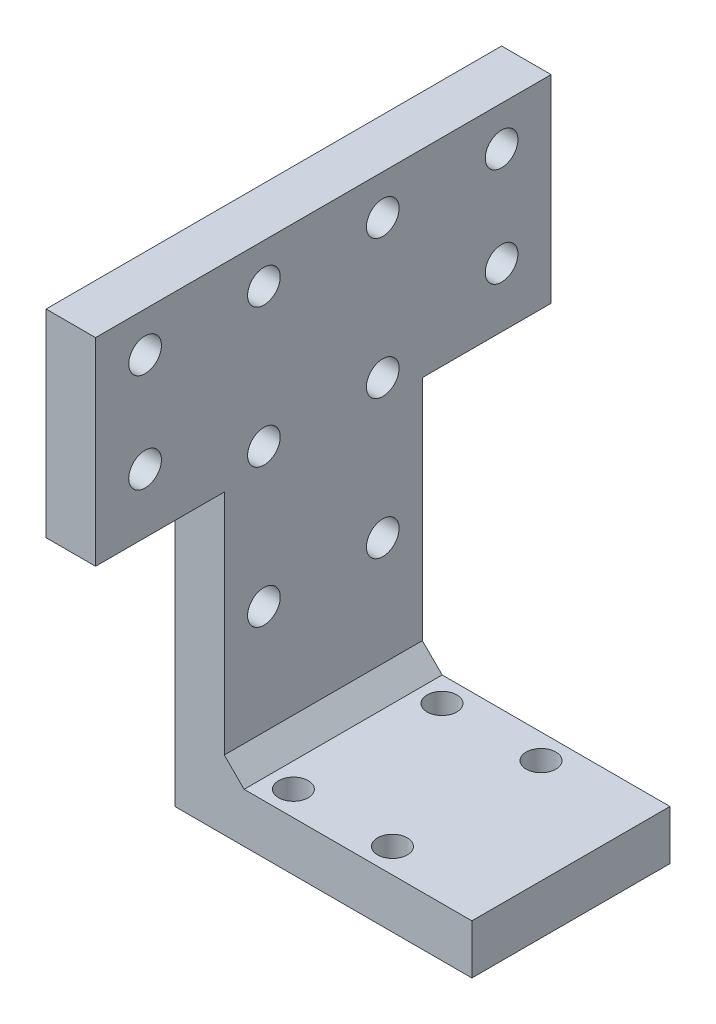
SolidWorks part; units mm, degrees
ref_plane "前视基准面" through (0, 0, 0) normal (0, 0, 1) x (1, 0, 0)
ref_plane "上视基准面" through (0, 0, 0) normal (0, 1, 0) x (1, 0, 0)
ref_plane "右视基准面" through (0, 0, 0) normal (1, 0, 0) x (0, 0, -1)
other "Configuration Table"
sketch "草图1" plane through (0, 0, 0) normal (0, 0, 1) x (1, 0, 0)
  line L0 (0, 50) -> (0, 0)
  line L1 (0, 0) -> (30, 0)
  line L2 (30, 0) -> (30, 5)
  line L3 (30, 5) -> (7, 5)
  line L4 (5, 7) -> (5, 50)
  line L5 (5, 50) -> (0, 50)
  line L6 (5, 7) -> (7, 5)
  dimension "D1" = 30
  dimension "D2" = 50
  dimension "D3" = 5
  dimension "D4" = 5
  dimension "D5" = 45
  dimension "D6" = 2
extrude "凸台-拉伸1" add sketch "草图1" along normal blind 20
sketch "草图2" plane through (0, 5, 0) normal (0, 1, 0) x (1, 0, 0)
  circle A1 centre (9.48, -17.5) radius 1.5
  circle A2 centre (9.48, -17.5) radius 1.5
  circle A3 centre (19.48, -17.5) radius 1.5
  circle A4 centre (19.48, -17.5) radius 1.5
  circle A5 centre (19.48, -2.5) radius 1.5
  circle A6 centre (19.48, -2.5) radius 1.5
  circle A7 centre (9.48, -2.5) radius 1.5
  circle A8 centre (9.48, -2.5) radius 1.5
  dimension "D1" = 0
  dimension "D2" = 0
  dimension "D3" = 0
  dimension "D4" = 0
sketch "草图3" plane through (5, 0, 0) normal (1, 0, 0) x (0, 0, -1)
  line L0 (-20, 50) -> (0, 50) construction
  line L1 (-4, 46) -> (-16, 46) construction
  line L2 (-4, 46) -> (-4, 32) construction
  line L3 (-4, 32) -> (-16, 32) construction
  line L4 (-16, 46) -> (-16, 32) construction
  line L5 (0, 7) -> (0, 50) construction
  line L6 (-20, 7) -> (-20, 50) construction
  circle A0 centre (-4, 46) radius 1.65
  circle A1 centre (-16, 46) radius 1.65
  circle A2 centre (-4, 32) radius 1.65
  circle A3 centre (-16, 32) radius 1.65
  circle A4 centre (-16, 18) radius 1.65
  circle A5 centre (-4, 18) radius 1.65
  dimension "D5" = 3.3
  dimension "D1" = 12
  dimension "D2" = 14
  dimension "D3" = 4
  dimension "D4" = 4
  dimension "D6" = 14
  dimension "D7" = 14
  dimension "D8" = 4
  dimension "D9" = 4
extrude "切除-拉伸2" cut sketch "草图3" against normal through all both
sketch "草图4" plane through (0, 0, 0) normal (-1, 0, 0) x (0, 0, 1)
  line L0 (20, 50) -> (33, 50)
  line L1 (33, 50) -> (33, 30)
  line L2 (33, 30) -> (20, 30)
  line L3 (20, 50) -> (20, 0) construction
  line L4 (0, 50) -> (-13, 50)
  line L5 (-13, 50) -> (-13, 30)
  line L6 (-13, 30) -> (0, 30)
  line L7 (0, 50) -> (0, 0) construction
  line L8 (20, 50) -> (20, 30)
  line L9 (0, 50) -> (0, 30)
  dimension "D1" = 13
  dimension "D2" = 13
  dimension "D3" = 20
  dimension "D4" = 20
extrude "凸台-拉伸2" add sketch "草图4" against normal blind 5
sketch "草图5" plane through (5, 0, 0) normal (1, 0, 0) x (0, 0, -1)
  line L0 (8, 46) -> (-28, 46) construction
  line L1 (-33, 50) -> (13, 50) construction
  line L2 (8, 36) -> (8, 46) construction
  line L3 (-28, 46) -> (-28, 36) construction
  circle A0 centre (-28, 46) radius 1.65
  circle A1 centre (-28, 36) radius 1.65
  circle A2 centre (8, 46) radius 1.65
  circle A3 centre (8, 36) radius 1.65
  circle A4 centre (-16, 46) radius 1.65 construction
  circle A5 centre (-4, 46) radius 1.65 construction
  circle A6 centre (-16, 32) radius 1.65 construction
  dimension "D1" = 4
  dimension "D2" = 12
  dimension "D3" = 12
  dimension "D4" = 10
  dimension "D5" = 10
extrude "切除-拉伸3" cut sketch "草图5" against normal through all both and the other way through all
extrude "切除-拉伸6" cut sketch "草图2" against normal through all both and the other way through all
